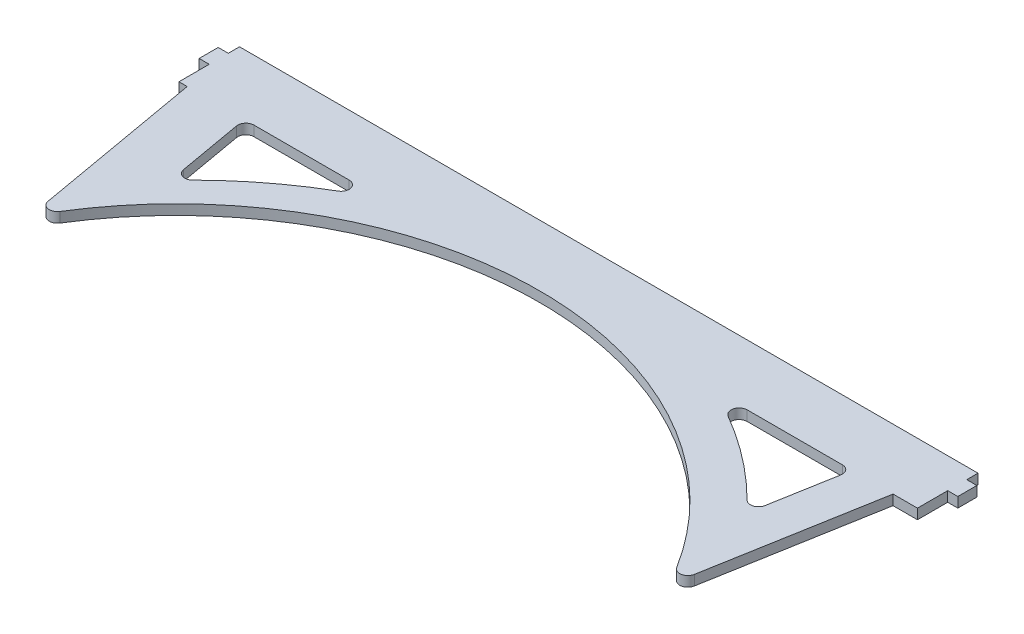
SolidWorks part; units mm, degrees
material "Balsa"
ref_plane "Front Plane" through (0, 0, 0) normal (0, 0, 1) x (1, 0, 0)
ref_plane "Top Plane" through (0, 0, 0) normal (0, 1, 0) x (1, 0, 0)
ref_plane "Right Plane" through (0, 0, 0) normal (1, 0, 0) x (0, 0, -1)
sketch "Sketch1" plane through (0, 0, 0) normal (0, 1, 0) x (1, 0, 0)
  line L1 (333.375, 9.525) -> (-333.375, 9.525)
  line L2 (333.375, 9.525) -> (333.375, -9.525)
  line L3 (333.375, -9.525) -> (-333.375, -9.525)
  line L4 (-333.375, 9.525) -> (-333.375, -9.525)
  line L5 (333.375, 9.525) -> (-333.375, -9.525) construction
  line L6 (333.375, -9.525) -> (-333.375, 9.525) construction
  point P0 (0, 0)
  dimension "D1" = 666.75
  dimension "D2" = 19.05
extrude "Boss-Extrude1" add sketch "Sketch1" along normal blind 3.175 contours L1 L4 L3 L2
sketch "Sketch2" plane through (0, 0, 0) normal (0, -1, 0) x (1, 0, 0)
  line L0 (333.375, 9.525) -> (-333.375, 9.525) construction
  line L1 (-333.375, 9.525) -> (-330.2, 9.525)
  line L2 (-333.375, 9.525) -> (-333.375, 0)
  line L3 (-333.375, 0) -> (-330.2, 0)
  line L4 (-330.2, 9.525) -> (-330.2, 0)
  line L5 (-119.3165, 9.525) -> (-116.1415, 9.525)
  line L6 (-119.3165, 9.525) -> (-119.3165, 0)
  line L7 (-119.3165, 0) -> (-116.1415, 0)
  line L8 (-116.1415, 9.525) -> (-116.1415, 0)
  line L9 (-333.375, -9.525) -> (-333.375, 9.525) construction
  point P14 (-333.375, 0)
  dimension "D1" = 217.2335
  dimension "D2" = 3.175
extrude "Cut-Extrude2" cut sketch "Sketch2" against normal through all
mirror "Mirror1" about plane through (0, 0, 0) normal (1, 0, 0) of "Cut-Extrude2"
sketch "Sketch3" plane through (0, 3.175, 0) normal (0, 1, 0) x (1, 0, 0)
  line L0 (108.4702, -9.525) -> (97.8994, -69.4753)
  line L1 (116.1415, -9.525) -> (-116.1415, -9.525) construction
  line L2 (97.8994, -69.4753) -> (80.4323, -39.2214) construction
  line L3 (97.8994, -69.4753) -> (70.7058, -69.4753) construction
  line L4 (-2.54, -9.525) -> (-2.54, 28.6639) construction
  line L5 (-113.5502, -9.525) -> (-102.9794, -69.4753)
  line L6 (-113.5502, -9.525) -> (108.4702, -9.525)
  circle A0 centre (-2.54, -124.0319) radius 114.3 construction
  arc A2 (97.8994, -69.4753) -> (-102.9794, -69.4753) centre (-2.54, -124.0319) ccw
  point P2 (-2.54, -9.525)
  dimension "D1" = 80
  dimension "D2" = 60
extrude "top ball securing" add sketch "Sketch3" against normal up to surface (3.175 mm away) up to face at (0, 0, 2.3812)
fillet "Fillet2" radius 2.54 2 edges at (97.8994, 1.5875, 69.4753) (-102.9794, 1.5875, 69.4753)
sketch "Sketch5" plane through (0, 3.175, 0) normal (0, 1, 0) x (1, 0, 0)
  line L1 (116.1415, -9.525) -> (108.4702, -9.525) construction
  line L2 (0, 9.525) -> (0, -17.0809) construction
  line L3 (333.375, 9.525) -> (-333.375, 9.525) construction
  line L5 (-91.4726, -32.787) -> (-95.0487, -12.5061)
  line L6 (-92.5473, -9.525) -> (-62.6062, -9.525)
  line L10 (92.5473, -9.525) -> (62.6062, -9.525)
  line L24 (86.5963, -60.4416) -> (95.9632, -7.3197)
  line L30 (91.4726, -32.787) -> (95.0487, -12.5061)
  arc A11 (61.3289, -14.2604) -> (62.6062, -9.525) centre (62.6062, -12.065) cw
  arc A12 (92.5473, -9.525) -> (95.0487, -12.5061) centre (92.5473, -12.065) cw
  arc A13 (105.223, -56.8297) -> (-110.303, -56.8297) centre (-2.54, -124.0319) ccw
  arc A14 (87.1768, -34.1437) -> (61.3289, -14.2604) centre (-2.54, -124.0319) ccw
  arc A15 (87.1768, -34.1437) -> (91.4726, -32.787) centre (88.9712, -32.3459) ccw
  arc A16 (-87.1768, -34.1437) -> (-91.4726, -32.787) centre (-88.9712, -32.3459) cw
  arc A17 (-87.1768, -34.1437) -> (-61.3289, -14.2604) centre (2.54, -124.0319) cw
  arc A18 (-92.5473, -9.525) -> (-95.0487, -12.5061) centre (-92.5473, -12.065) ccw
  arc A19 (-61.3289, -14.2604) -> (-62.6062, -9.525) centre (-62.6062, -12.065) ccw
  dimension "D2" = 12.7
  dimension "D3" = 2.54
  dimension "D1" = 12.7
extrude "Cut-Extrude3" cut sketch "Sketch5" against normal through all
sketch "Sketch4" [suppressed] plane through (0, 3.175, 0) normal (0, 1, 0) x (1, 0, 0)
  line L0 (326.6153, -9.525) -> (316.7271, -65.6036)
  line L1 (339.725, -9.525) -> (128.5875, -9.525) construction
  line L2 (318.0792, -67.215) -> (294.4042, -39.0001) construction
  line L3 (316.7271, -65.6036) -> (297.9729, -65.6036) construction
  line L4 (228.6, -24.5093) -> (228.6, -9.525) construction
  line L5 (130.5847, -9.525) -> (140.4729, -65.6036)
  line L6 (326.6153, -9.525) -> (130.5847, -9.525)
  arc A3 (316.7271, -65.6036) -> (140.4729, -65.6036) centre (228.6, -139.5511) ccw
  dimension "D3" = 13.1097
  dimension "D1" = 80
  dimension "D2" = 50
  dimension "D4" = 1.9972
  dimension "D5" = 14.9843
  dimension "D6" = 80
extrude "Boss-Extrude2" [suppressed] add sketch "Sketch4" against normal up to surface (3.175 mm away)
sketch "Sketch6" [suppressed] plane through (0, 3.175, 0) normal (0, 1, 0) x (1, 0, 0)
  line L0 (339.725, -9.525) -> (326.6153, -9.525) construction
  line L1 (242.8327, -9.525) -> (310.6923, -9.525)
  line L17 (304.2201, -63.3983) -> (314.1082, -7.3197)
  line L18 (309.1131, -35.6488) -> (313.1937, -12.5061)
  line L19 (146.5077, -9.525) -> (214.3673, -9.525)
  line L20 (143.0918, -7.3197) -> (152.9799, -63.3983)
  line L21 (144.0063, -12.5061) -> (148.0869, -35.6488)
  line L22 (228.6, -15.2969) -> (228.6, 9.525) construction
  line L23 (342.9, 9.525) -> (-342.9, 9.525) construction
  arc A0 (214.3673, -9.525) -> (214.5363, -12.5858) centre (214.3673, -11.0601) cw
  arc A1 (214.5363, -12.5858) -> (152.1093, -37.242) centre (228.6, -139.5511) ccw
  arc A2 (310.6923, -9.525) -> (313.1937, -12.5061) centre (310.6923, -12.065) cw
  arc A3 (309.1131, -35.6488) -> (305.0907, -37.242) centre (306.6116, -35.2077) cw
  arc A4 (152.1093, -37.242) -> (148.0869, -35.6488) centre (150.5884, -35.2077) cw
  arc A5 (144.0063, -12.5061) -> (146.5077, -9.525) centre (146.5077, -12.065) cw
  arc A6 (242.8327, -9.525) -> (242.6637, -12.5858) centre (242.8327, -11.0601) ccw
  arc A7 (326.4559, -57.4402) -> (130.7441, -57.4402) centre (228.6, -139.5511) ccw
  arc A8 (305.0907, -37.242) -> (242.6637, -12.5858) centre (228.6, -139.5511) ccw
  point P17 (241.3, -10.9754)
  dimension "D5" = 2.54
  dimension "D4" = 12.7
  dimension "D1" = 12.7
  dimension "D2" = 12.7
  dimension "D3" = 12.7
extrude "Cut-Extrude4" [suppressed] cut sketch "Sketch6" against normal through all both and the other way through all
fillet "Fillet1" [suppressed] radius 2.54
sketch "Sketch7" [suppressed] plane through (0, 3.175, 0) normal (0, 1, 0) x (1, 0, 0)
  line L0 (228.6, -24.5093) -> (228.6, 2.3574) construction
  line L1 (227.0125, -18.1702) -> (230.1875, -18.1702)
  line L2 (230.1875, -18.1702) -> (230.1875, -24.5202)
  line L3 (227.0125, -18.1702) -> (227.0125, -24.5202)
  arc A0 (313.2745, -61.674) -> (143.9255, -61.674) centre (228.6, -139.5511) ccw construction
  arc A2 (227.0125, -24.5202) -> (230.1875, -24.5202) centre (228.6, -139.5511) cw
  point P13 (228.6, -18.1702)
  dimension "D1" = 1.5875
  dimension "D2" = 6.35
extrude "Cut-Extrude5" [suppressed] cut sketch "Sketch7" against normal through all both and the other way through all contours L2 A2 L3 L1
mirror "Mirror2" [suppressed] about plane through (0, 0, 0) normal (1, 0, 0)
sketch "Sketch12" plane through (0, 0, 0) normal (0, -1, 0) x (1, 0, 0)
  line L0 (333.375, -9.525) -> (-333.375, -9.525) construction
  line L1 (119.3165, -9.525) -> (333.375, -9.525)
  line L2 (119.3165, -9.525) -> (119.3165, 9.525)
  line L3 (119.3165, 9.525) -> (333.375, 9.525)
  line L4 (333.375, -9.525) -> (333.375, 9.525)
  line L5 (119.3165, 9.525) -> (119.3165, 0) construction
  line L6 (330.2, 9.525) -> (119.3165, 9.525) construction
  line L7 (333.375, -9.525) -> (333.375, 0) construction
  line L8 (0, 0) -> (0, -67.8507) construction
  line L9 (-119.3165, 9.525) -> (-333.375, 9.525)
  line L10 (-333.375, -9.525) -> (-333.375, 9.525)
  line L11 (-119.3165, -9.525) -> (-333.375, -9.525)
  line L12 (-119.3165, -9.525) -> (-119.3165, 9.525)
extrude "Cut-Extrude8" cut sketch "Sketch12" against normal up to next
sketch "Sketch13" plane through (0, 0, 0) normal (0, -1, 0) x (1, 0, 0)
  line L0 (0, 0) -> (0, -39.7063) construction
  line L1 (119.3165, -9.525) -> (116.1415, -9.525)
  line L2 (119.3165, -9.525) -> (119.3165, -5.9925)
  line L3 (119.3165, -5.9925) -> (116.1415, -5.9925)
  line L4 (116.1415, -9.525) -> (116.1415, -5.9925)
  line L5 (-119.3165, -5.9925) -> (-116.1415, -5.9925)
  line L6 (-116.1415, -9.525) -> (-116.1415, -5.9925)
  line L7 (-119.3165, -9.525) -> (-116.1415, -9.525)
  line L8 (-119.3165, -9.525) -> (-119.3165, -5.9925)
  dimension "D1" = 3.175
  dimension "D2" = 3.5325
extrude "Cut-Extrude9" cut sketch "Sketch13" against normal up to next
